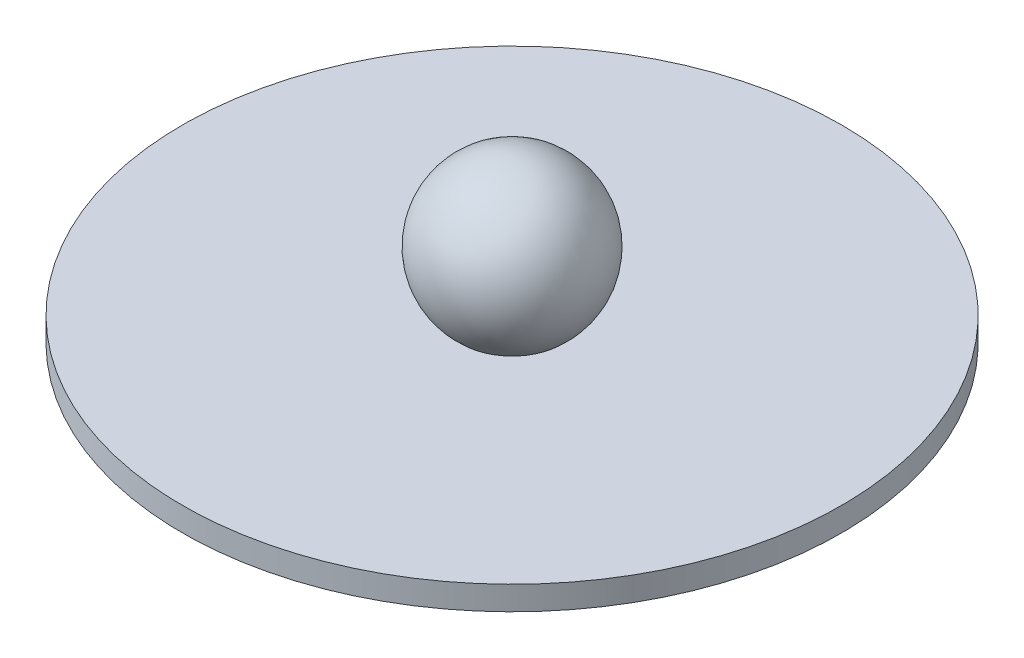
SolidWorks part; units mm, degrees
ref_plane "Front" through (0, 0, 0) normal (0, 0, 1) x (1, 0, 0)
ref_plane "Top" through (0, 0, 0) normal (0, 1, 0) x (1, 0, 0)
ref_plane "Right" through (0, 0, 0) normal (1, 0, 0) x (0, 0, -1)
sketch "Sketch1" plane through (0, 0, 0) normal (0, 0, 1) x (1, 0, 0)
  line L0 (0, 0) -> (0, 90.5826) construction
  line L1 (80.645, 12.7) -> (80.645, 6.858)
  line L2 (80.645, 6.858) -> (75.565, 6.858)
  line L3 (75.565, 6.858) -> (68.707, 0)
  line L4 (68.707, 0) -> (0, 0)
  line L5 (0, 0) -> (0, 12.7)
  line L6 (0, 12.7) -> (80.645, 12.7)
  dimension "D1" = 80.645
  dimension "D2" = 12.7
  dimension "D3" = 45
  dimension "D4" = 5.842
  dimension "D5" = 5.08
revolve "Revolve1" add sketch "Sketch1" angle 360 about L0
sketch "Sketch2" plane through (0, 0, 0) normal (0, 0, 1) x (1, 0, 0)
  line L0 (0, 0) -> (0, 27.2643) construction
  line L1 (0, 46.3143) -> (0, 8.2143)
  arc A0 (0, 8.2143) -> (0, 46.3143) centre (0, 27.2643) ccw
  dimension "D1" = 38.1
revolve "Revolve2" add sketch "Sketch2" angle 360 about L0
